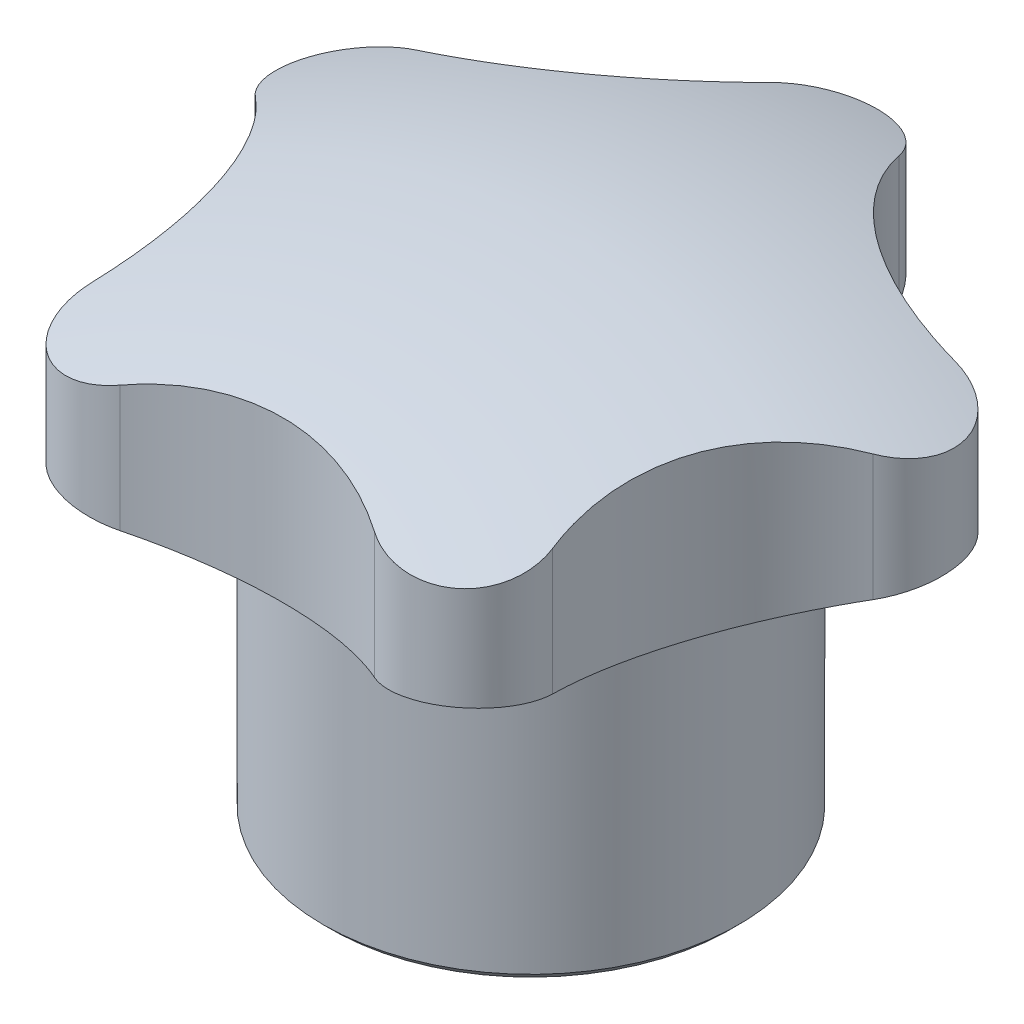
SolidWorks part; units mm, degrees
ref_plane "前视基准面" through (0, 0, 0) normal (0, 0, 1) x (1, 0, 0)
ref_plane "上视基准面" through (0, 0, 0) normal (0, 1, 0) x (1, 0, 0)
ref_plane "右视基准面" through (0, 0, 0) normal (1, 0, 0) x (0, 0, -1)
sketch "草图1" plane through (0, 0, 0) normal (0, 0, 1) x (1, 0, 0)
  line L0 (0, 0) -> (0, 85.8527) construction
  line L1 (0, 0) -> (-7.5, 0)
  line L2 (-7.5, 0) -> (-7.5, 10.8)
  line L3 (-12.5, 15.7959) -> (-12.5, 12.0784)
  line L4 (0, 18) -> (0, 0)
  line L5 (-12.5, 15.7959) -> (0, 20.3455) construction
  line L6 (-12.5, 12.0784) -> (0, 8.0169) construction
  arc A0 (0, 18) -> (-12.5, 15.7959) centre (0, -18.5476) ccw
  arc A1 (-12.5, 12.0784) -> (-7.5, 10.8) centre (0, 50.5495) ccw
  dimension "D1" = 18
  dimension "D2" = 15
  dimension "D3" = 25
  dimension "D4" = 70
  dimension "D5" = 72
  dimension "D6" = 10.8
revolve "旋转1" add sketch "草图1" angle 360 about L4
sketch "草图2" plane through (0, 0, 0) normal (0, 1, 0) x (1, 0, 0)
  line L0 (0, 0) -> (0, 18.5989) construction
  line L1 (-7.3473, 10.1127) -> (-4.4084, 6.0676) construction
  arc A0 (2.3013, 10.9768) -> (-2.3013, 10.9768) centre (0, 10) ccw
  circle A1 centre (0, 0) radius 7.5 construction
  circle A2 centre (0, 0) radius 12.5 construction
  arc A3 (11.1507, 1.2033) -> (9.7284, 5.5807) centre (9.5106, 3.0902) ccw
  arc A4 (4.5902, -10.233) -> (8.3138, -7.5277) centre (5.8779, -8.0902) ccw
  arc A5 (-8.3138, -7.5277) -> (-4.5902, -10.233) centre (-5.8779, -8.0902) ccw
  arc A6 (-9.7284, 5.5807) -> (-11.1507, 1.2033) centre (-9.5106, 3.0902) ccw
  arc A7 (-9.7284, 5.5807) -> (-2.3013, 10.9768) centre (-10.5048, 14.4587) ccw
  arc A8 (2.3013, 10.9768) -> (9.7284, 5.5807) centre (10.5048, 14.4587) ccw
  arc A9 (11.1507, 1.2033) -> (8.3138, -7.5277) centre (16.9972, -5.5227) ccw
  arc A10 (4.5902, -10.233) -> (-4.5902, -10.233) centre (0, -17.8719) ccw
  arc A11 (-8.3138, -7.5277) -> (-11.1507, 1.2033) centre (-16.9972, -5.5227) ccw
  circle A12 centre (0, 0) radius 13.5
  circle A13 centre (0, 0) radius 8.96 construction
  point P20 (0, 0)
  point P22 (-5.2666, 7.2488)
  point P38 (0, 0)
  dimension "D4" = 1
  dimension "D5" = 17.92
  dimension "D2" = 36
  dimension "D1" = 5
  dimension "D3" = 5
extrude "切除-拉伸1" cut sketch "草图2" along normal through all
sketch "草图3" plane through (0, 0, 0) normal (0, 0, 1) x (1, 0, 0)
  line L0 (0, 0) -> (0, 20.3351) construction
  line L1 (0, 0) -> (0, 12)
  line L2 (2.58, 12) -> (0, 12)
  line L3 (2.58, 12) -> (2.58, 0)
  line L4 (-7.5, 0) -> (7.5, 0) construction
  line L5 (2.58, 0) -> (0, 0)
  dimension "D1" = 5.16
  dimension "D3" = 12
revolve "切除-旋转1" cut sketch "草图3" angle 360 about L0
cosmetic thread "装饰螺纹线1" parameters "D2"=6
sketch "草图4" plane through (0, 0, 0) normal (0, -1, 0) x (1, 0, 0)
  circle A0 centre (0, 0) radius 3
  dimension "D1" = 6
extrude "凸台-拉伸1" [suppressed] add sketch "草图4" along normal blind 10
cosmetic thread "装饰螺纹线2" [suppressed] parameters "D2"=5.16
chamfer "倒角2" [suppressed] distance 0.6 angle 45
chamfer "倒角1" distance 0.3 angle 45 1 edges at (0, 0, 7.5)
